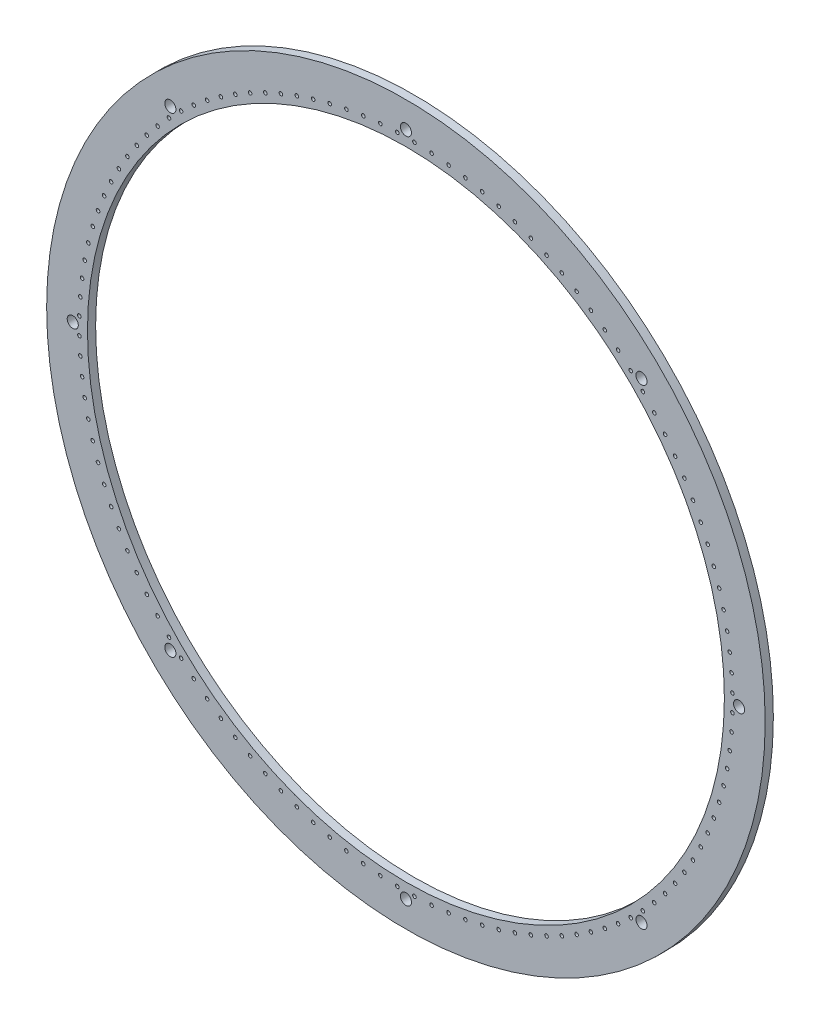
SolidWorks part; units mm, degrees
ref_plane "Front Plane" through (0, 0, 0) normal (0, 0, 1) x (1, 0, 0)
ref_plane "Top Plane" through (0, 0, 0) normal (0, 1, 0) x (1, 0, 0)
ref_plane "Right Plane" through (0, 0, 0) normal (1, 0, 0) x (0, 0, -1)
sketch "Sketch1" plane through (0, 0, 0) normal (0, 0, 1) x (1, 0, 0)
  line L0 (191.77, -116.6414) -> (191.77, -17.2855)
  line L1 (175.6086, 1.25) -> (173.6914, 1.25)
  line L2 (173.6914, -1.25) -> (175.6086, -1.25)
  line L3 (182.9414, -7.079) -> (182.9414, -9.079)
  line L4 (185.4414, -7.079) -> (185.4414, -9.079) construction
  line L5 (194.6086, -1.25) -> (192.6914, -1.25)
  line L6 (192.6914, 1.25) -> (194.6086, 1.25)
  line L7 (185.4, 6.921) -> (185.4, 8.9209)
  line L8 (182.9, 8.9209) -> (182.9, 6.921)
  line L9 (182.9414, -7.079) -> (182.9414, -9.079)
  line L10 (185.4414, -9.079) -> (185.4414, -7.079)
  line L12 (201.4355, -7.62) -> (300.7914, -7.62)
  line L14 (300.7914, 7.62) -> (201.4355, 7.62)
  line L15 (191.77, -0.8447) -> (191.77, 0.8447)
  line L16 (191.77, 17.2855) -> (191.77, 116.6414)
  line L17 (176.53, -116.6414) -> (176.53, -17.2855)
  line L18 (191.77, -123.5903) -> (191.77, -13.9266)
  line L19 (176.53, 17.2855) -> (176.53, 116.6414)
  line L20 (54.61, 0) -> (60.325, 0)
  line L21 (57.1935, -3.3245) -> (60.3674, -3.2414)
  arc A0 (169.4249, 122.9463) -> (169.4249, -122.9463) centre (184.15, 0) ccw
  arc A9 (173.6914, -1.25) -> (173.6914, 1.25) centre (173.6914, 0) cw
  arc A10 (173.6914, 1.25) -> (173.6914, -1.25) centre (173.6914, 0) ccw construction
  arc A11 (175.6086, -1.25) -> (175.6086, 1.25) centre (175.6086, 0) ccw
  arc A12 (175.6086, -1.25) -> (175.6086, 1.25) centre (175.6086, 0) ccw construction
  arc A13 (182.9414, -9.079) -> (185.4414, -9.079) centre (184.1914, -9.079) ccw
  arc A14 (185.4414, -7.079) -> (182.9414, -7.079) centre (184.1914, -7.079) ccw
  arc A15 (185.4414, -7.079) -> (182.9414, -7.079) centre (184.1914, -7.079) ccw construction
  arc A16 (182.9, 6.921) -> (185.4, 6.921) centre (184.15, 6.921) ccw
  arc A17 (182.9, 6.921) -> (185.4, 6.921) centre (184.15, 6.921) ccw construction
  arc A18 (185.4, 8.9209) -> (182.9, 8.9209) centre (184.15, 8.9209) ccw
  arc A19 (185.4, 8.9209) -> (182.9, 8.9209) centre (184.15, 8.9209) ccw construction
  arc A20 (194.6086, -1.25) -> (194.6086, 1.25) centre (194.6086, 0) ccw
  arc A21 (194.6086, -1.25) -> (194.6086, 1.25) centre (194.6086, 0) ccw construction
  arc A22 (192.6914, -1.25) -> (192.6914, 1.25) centre (192.6914, 0) cw
  arc A23 (192.6914, 1.25) -> (192.6914, -1.25) centre (192.6914, 0) ccw construction
  arc A24 (194.1286, -12.3468) -> (196.4968, -9.9786) centre (184.15, 0) ccw
  circle A25 centre (184.15, 0) radius 139.7
  circle A26 centre (313.69, 0) radius 2.159
  circle A27 centre (313.69, 0) radius 2.159
  circle A28 centre (275.7486, -91.5986) radius 2.159
  circle A29 centre (184.15, -129.54) radius 2.159
  circle A30 centre (92.5514, -91.5986) radius 2.159
  circle A39 centre (57.1935, -3.3245) radius 0.6985
  circle A40 centre (184.15, 0) radius 5.08 construction
  circle A41 centre (57.1935, 3.3245) radius 0.6985
  circle A42 centre (57.5415, 9.9643) radius 0.6985
  circle A43 centre (58.2365, 16.5768) radius 0.6985
  circle A44 centre (59.2766, 23.1439) radius 0.6985
  circle A45 centre (60.659, 29.6476) radius 0.6985
  circle A46 centre (62.3799, 36.0699) radius 0.6985
  circle A47 centre (64.4345, 42.3935) radius 0.6985
  circle A48 centre (66.8173, 48.6008) radius 0.6985
  circle A49 centre (69.5217, 54.6749) radius 0.6985
  circle A50 centre (72.5402, 60.5992) radius 0.6985
  circle A51 centre (75.8647, 66.3573) radius 0.6985
  circle A52 centre (79.486, 71.9336) radius 0.6985
  circle A53 centre (83.3941, 77.3127) radius 0.6985
  circle A54 centre (87.5784, 82.4799) radius 0.6985
  circle A55 centre (92.0275, 87.421) radius 0.6985
  circle A56 centre (96.729, 92.1225) radius 0.6985
  circle A57 centre (101.6701, 96.5716) radius 0.6985
  circle A58 centre (106.8373, 100.7559) radius 0.6985
  circle A59 centre (112.2164, 104.664) radius 0.6985
  circle A60 centre (117.7927, 108.2853) radius 0.6985
  circle A61 centre (123.5508, 111.6098) radius 0.6985
  circle A62 centre (129.4751, 114.6283) radius 0.6985
  circle A63 centre (135.5492, 117.3327) radius 0.6985
  circle A64 centre (141.7565, 119.7155) radius 0.6985
  circle A65 centre (148.0801, 121.7701) radius 0.6985
  circle A66 centre (154.5024, 123.491) radius 0.6985
  circle A67 centre (161.0061, 124.8734) radius 0.6985
  circle A68 centre (167.5732, 125.9135) radius 0.6985
  circle A69 centre (174.1857, 126.6085) radius 0.6985
  circle A70 centre (180.8255, 126.9565) radius 0.6985
  circle A71 centre (187.4745, 126.9565) radius 0.6985
  circle A72 centre (194.1143, 126.6085) radius 0.6985
  circle A73 centre (200.7268, 125.9135) radius 0.6985
  circle A74 centre (207.2939, 124.8734) radius 0.6985
  circle A75 centre (213.7976, 123.491) radius 0.6985
  circle A76 centre (220.2199, 121.7701) radius 0.6985
  circle A77 centre (226.5435, 119.7155) radius 0.6985
  circle A78 centre (232.7508, 117.3327) radius 0.6985
  circle A79 centre (238.8249, 114.6283) radius 0.6985
  circle A80 centre (244.7492, 111.6098) radius 0.6985
  circle A81 centre (250.5073, 108.2853) radius 0.6985
  circle A82 centre (256.0836, 104.664) radius 0.6985
  circle A83 centre (261.4627, 100.7559) radius 0.6985
  circle A84 centre (266.6299, 96.5716) radius 0.6985
  circle A85 centre (271.571, 92.1225) radius 0.6985
  circle A86 centre (276.2725, 87.421) radius 0.6985
  circle A87 centre (280.7216, 82.4799) radius 0.6985
  circle A88 centre (284.9059, 77.3127) radius 0.6985
  circle A89 centre (288.814, 71.9336) radius 0.6985
  circle A90 centre (292.4353, 66.3573) radius 0.6985
  circle A91 centre (295.7598, 60.5992) radius 0.6985
  circle A92 centre (298.7783, 54.6749) radius 0.6985
  circle A93 centre (301.4827, 48.6008) radius 0.6985
  circle A94 centre (303.8655, 42.3935) radius 0.6985
  circle A95 centre (305.9201, 36.0699) radius 0.6985
  circle A96 centre (307.641, 29.6476) radius 0.6985
  circle A97 centre (309.0234, 23.1439) radius 0.6985
  circle A98 centre (310.0635, 16.5768) radius 0.6985
  circle A99 centre (310.7585, 9.9643) radius 0.6985
  circle A100 centre (311.1065, 3.3245) radius 0.6985
  circle A101 centre (311.1065, -3.3245) radius 0.6985
  circle A102 centre (310.7585, -9.9643) radius 0.6985
  circle A103 centre (310.0635, -16.5768) radius 0.6985
  circle A104 centre (309.0234, -23.1439) radius 0.6985
  circle A105 centre (307.641, -29.6476) radius 0.6985
  circle A106 centre (305.9201, -36.0699) radius 0.6985
  circle A107 centre (303.8655, -42.3935) radius 0.6985
  circle A108 centre (301.4827, -48.6008) radius 0.6985
  circle A109 centre (298.7783, -54.6749) radius 0.6985
  circle A110 centre (295.7598, -60.5992) radius 0.6985
  circle A111 centre (292.4353, -66.3573) radius 0.6985
  circle A112 centre (288.814, -71.9336) radius 0.6985
  circle A113 centre (284.9059, -77.3127) radius 0.6985
  circle A114 centre (280.7216, -82.4799) radius 0.6985
  circle A115 centre (276.2725, -87.421) radius 0.6985
  circle A116 centre (271.571, -92.1225) radius 0.6985
  circle A117 centre (266.6299, -96.5716) radius 0.6985
  circle A118 centre (261.4627, -100.7559) radius 0.6985
  circle A119 centre (256.0836, -104.664) radius 0.6985
  circle A120 centre (250.5073, -108.2853) radius 0.6985
  circle A121 centre (244.7492, -111.6098) radius 0.6985
  circle A122 centre (238.8249, -114.6283) radius 0.6985
  circle A123 centre (232.7508, -117.3327) radius 0.6985
  circle A124 centre (226.5435, -119.7155) radius 0.6985
  circle A125 centre (220.2199, -121.7701) radius 0.6985
  circle A126 centre (213.7976, -123.491) radius 0.6985
  circle A127 centre (207.2939, -124.8734) radius 0.6985
  circle A128 centre (200.7268, -125.9135) radius 0.6985
  circle A129 centre (194.1143, -126.6085) radius 0.6985
  circle A130 centre (187.4745, -126.9565) radius 0.6985
  circle A131 centre (180.8255, -126.9565) radius 0.6985
  circle A132 centre (174.1857, -126.6085) radius 0.6985
  circle A133 centre (167.5732, -125.9135) radius 0.6985
  circle A134 centre (161.0061, -124.8734) radius 0.6985
  circle A135 centre (154.5024, -123.491) radius 0.6985
  circle A136 centre (148.0801, -121.7701) radius 0.6985
  circle A137 centre (141.7565, -119.7155) radius 0.6985
  circle A138 centre (135.5492, -117.3327) radius 0.6985
  circle A139 centre (129.4751, -114.6283) radius 0.6985
  circle A140 centre (123.5508, -111.6098) radius 0.6985
  circle A141 centre (117.7927, -108.2853) radius 0.6985
  circle A142 centre (112.2164, -104.664) radius 0.6985
  circle A143 centre (106.8373, -100.7559) radius 0.6985
  circle A144 centre (101.6701, -96.5716) radius 0.6985
  circle A145 centre (96.729, -92.1225) radius 0.6985
  circle A146 centre (92.0275, -87.421) radius 0.6985
  circle A147 centre (87.5784, -82.4799) radius 0.6985
  circle A148 centre (83.3941, -77.3127) radius 0.6985
  circle A149 centre (79.486, -71.9336) radius 0.6985
  circle A150 centre (75.8647, -66.3573) radius 0.6985
  circle A151 centre (72.5402, -60.5992) radius 0.6985
  circle A152 centre (69.5217, -54.6749) radius 0.6985
  circle A153 centre (66.8173, -48.6008) radius 0.6985
  circle A154 centre (64.4345, -42.3935) radius 0.6985
  circle A155 centre (62.3799, -36.0699) radius 0.6985
  circle A156 centre (60.659, -29.6476) radius 0.6985
  circle A157 centre (59.2766, -23.1439) radius 0.6985
  circle A158 centre (58.2365, -16.5768) radius 0.6985
  circle A159 centre (57.5415, -9.9643) radius 0.6985
  arc A161 (196.4968, 9.9786) -> (194.1286, 12.3468) centre (184.15, 0) ccw
  arc A162 (174.1714, 12.3468) -> (174.1714, -12.3468) centre (184.15, 0) ccw
  arc A163 (198.0766, 7.62) -> (191.77, 13.9266) centre (184.15, 0) ccw
  arc A164 (191.77, -13.9266) -> (198.0766, -7.62) centre (184.15, 0) ccw
  circle A165 centre (184.15, 0) radius 5.08
  arc A166 (198.8751, -122.9463) -> (307.0963, -14.7251) centre (184.15, 0) ccw
  arc A167 (307.0963, 14.7251) -> (198.8751, 122.9463) centre (184.15, 0) ccw
  arc A168 (198.8751, -122.9463) -> (191.77, -116.6414) centre (198.12, -116.6414) cw
  arc A169 (169.4249, -122.9463) -> (176.53, -116.6414) centre (170.18, -116.6414) ccw
  arc A170 (176.53, 116.6414) -> (169.4249, 122.9463) centre (170.18, 116.6414) ccw
  arc A171 (198.8751, 122.9463) -> (191.77, 116.6414) centre (198.12, 116.6414) ccw
  arc A172 (307.0963, -14.7251) -> (300.7914, -7.62) centre (300.7914, -13.97) ccw
  arc A173 (307.0963, 14.7251) -> (300.7914, 7.62) centre (300.7914, 13.97) cw
  arc A174 (174.1714, -12.3468) -> (176.53, -17.2855) centre (170.18, -17.2855) cw
  arc A175 (194.1286, -12.3468) -> (191.77, -17.2855) centre (198.12, -17.2855) ccw
  arc A176 (196.4968, -9.9786) -> (201.4355, -7.62) centre (201.4355, -13.97) cw
  arc A177 (196.4968, 9.9786) -> (201.4355, 7.62) centre (201.4355, 13.97) ccw
  arc A178 (194.1286, 12.3468) -> (191.77, 17.2855) centre (198.12, 17.2855) cw
  arc A179 (174.1714, 12.3468) -> (176.53, 17.2855) centre (170.18, 17.2855) ccw
  circle A180 centre (54.61, 0) radius 2.159
  circle A181 centre (92.5514, 91.5986) radius 2.159
  circle A182 centre (184.15, 129.54) radius 2.159
  circle A183 centre (275.7486, 91.5986) radius 2.159
  point P106 (184.15, 0)
  point P357 (184.15, 0)
  point P364 (307.7403, -7.62)
  point P367 (307.7403, 7.62)
  dimension "D1" = 247.65
  dimension "D2" = 279.4
  dimension "D7" = 4.318
  dimension "D9" = 8
  dimension "D10" = 1.397
  dimension "D11" = 127
  dimension "D3" = 6.35
  dimension "D4" = 6.35
  dimension "D8" = 129.54
  dimension "D12" = 1.5
  dimension "D13" = 120
extrude "Boss-Extrude1" add sketch "Sketch1" along normal blind 3.175 contours A25 A159 A158 A157 A156 A155 A154 A153 A152 A151 A150 A149 A148 A147 A146 A145 A144 A143 A142 A141 A140 A139 A138 A137 A136 A135
sketch "Sketch2" plane through (0, 0, 3.175) normal (0, 0, 1) x (1, 0, 0)
  circle A0 centre (184.15, 0) radius 123.825
extrude "Cut-Extrude1" cut sketch "Sketch2" against normal through all
